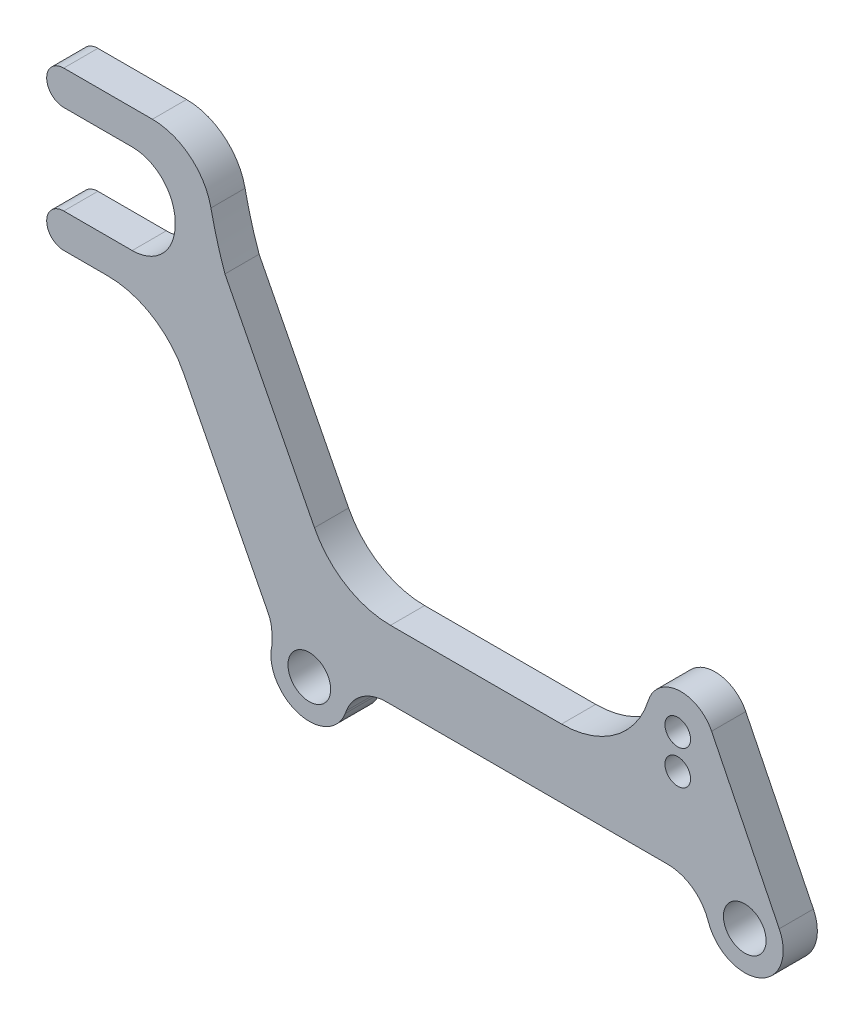
SolidWorks part; units mm, degrees
ref_plane "Front Plane" through (0, 0, 0) normal (0, 0, 1) x (1, 0, 0)
ref_plane "Top Plane" through (0, 0, 0) normal (0, 1, 0) x (1, 0, 0)
ref_plane "Right Plane" through (0, 0, 0) normal (1, 0, 0) x (0, 0, -1)
sketch "Sketch1" plane through (0, 0, 0) normal (0, 0, 1) x (1, 0, 0)
  line L0 (9.0217, 2) -> (41.9783, 2)
  line L1 (25.5, 14.9964) -> (25.5, -11.2721) construction
  line L2 (9.5048, 10.0021) -> (29.5383, 10.0021)
  line L3 (47.1152, 18.0606) -> (55.0364, 1.9894)
  line L4 (-4.3859, 1.0071) -> (-4.3847, 2.2692)
  line L5 (-4.8234, 4.0941) -> (-14.7192, 23.4447)
  line L6 (-4.3859, 1.0071) -> (-4.3839, 3.2346) construction
  line L7 (0.6015, 15.449) -> (-9.8806, 35.9461)
  line L8 (5.6141, 0.9982) -> (5.6183, 5.639) construction
  line L9 (-4.3839, 3.2346) -> (-15.5453, 25.06) construction
  line L10 (5.6183, 5.639) -> (-6.642, 29.6132) construction
  line L11 (-23.6226, 28.8915) -> (-28.7602, 28.8915)
  line L13 (-28.7602, 47.3915) -> (-18.3776, 47.3915)
  line L14 (-28.7602, 43.3915) -> (-20.7438, 43.3915)
  line L15 (-23.6226, 32.8915) -> (-28.7602, 32.8915)
  line L16 (-23.6226, 32.8915) -> (-20.7438, 32.8915)
  line L17 (-28.7602, 43.3915) -> (-28.7602, 32.8915) construction
  line L18 (-28.7602, 38.1415) -> (-33.6393, 38.1415) construction
  line L19 (-28.7602, 43.3915) -> (-18.3776, 43.3915) construction
  line L20 (46.6567, -1.2359) -> (46.7894, -1.5877)
  line L21 (4.3433, -1.2359) -> (4.2106, -1.5877)
  circle A0 centre (0, 0) radius 2.5
  circle A1 centre (51, 0) radius 2.5
  arc A2 (-4.3859, 1.0071) -> (4.2106, -1.5877) centre (0, 0) ccw
  arc A3 (46.7894, -1.5877) -> (55.0364, 1.9894) centre (51, 0) ccw
  circle A6 centre (43.1502, 12) radius 1.5
  circle A7 centre (43.1502, 16) radius 1.5
  arc A8 (47.1152, 18.0606) -> (39.7088, 17.4834) centre (43.5274, 16.2922) ccw
  arc A9 (39.7088, 17.4834) -> (29.5383, 10.0021) centre (29.5383, 20.656) cw
  arc A10 (-4.3847, 2.2692) -> (-4.8234, 4.0941) centre (-8.3847, 2.2728) ccw
  circle A11 centre (51, 0) radius 4.5 construction
  arc A12 (9.5048, 10.0021) -> (0.6015, 15.449) centre (9.5048, 20.0021) cw
  circle A14 centre (0, 0) radius 4.5 construction
  arc A15 (-14.7192, 23.4447) -> (-23.6226, 28.8915) centre (-23.6226, 18.8915) ccw
  arc A16 (-11.5244, 41.8176) -> (-18.3776, 47.3915) centre (-18.3776, 40.3915) ccw
  arc A17 (-16.0925, 40.2261) -> (-16.0925, 36.0569) centre (-21.3776, 38.1415) cw
  arc A18 (-15.3776, 40.3915) -> (-18.3776, 43.3915) centre (-18.3776, 40.3915) ccw construction
  arc A19 (-28.7602, 47.3915) -> (-28.7602, 43.3915) centre (-28.7602, 45.3915) ccw
  arc A20 (-28.7602, 28.8915) -> (-28.7602, 32.8915) centre (-28.7602, 30.8915) cw
  arc A21 (-16.0925, 36.0569) -> (-20.7438, 32.8915) centre (-20.7438, 37.8915) cw
  arc A22 (-20.7438, 43.3915) -> (-16.0925, 40.2261) centre (-20.7438, 38.3915) cw
  arc A23 (-11.3776, 40.3915) -> (-18.3776, 47.3915) centre (-18.3776, 40.3915) ccw construction
  arc A24 (-9.8806, 35.9461) -> (-11.5244, 41.8176) centre (32.5318, 50.9854) cw
  arc A25 (4.3433, -1.2359) -> (9.0217, 2) centre (9.0217, -3) cw
  arc A26 (46.6567, -1.2359) -> (41.9783, 2) centre (41.9783, -3) ccw
  point P9 (3.6661, 2.5112)
  point P10 (47.3339, 2.5112)
  point P25 (25.5, 2)
  point P33 (55.5, 0)
  point P36 (4.5, 0)
  point P47 (5.5634, 2)
  point P75 (45.4366, 2)
  point P76 (0, 0)
  point P77 (0, 0)
  dimension "D1" = 5
  dimension "D2" = 3
  dimension "D6" = 10
  dimension "D7" = 4
  dimension "D8" = 4
  dimension "D9" = 10
  dimension "D11" = 45
  dimension "D10" = 7
  dimension "D15" = 4
  dimension "D16" = 5
  dimension "D14" = 5
  dimension "D3" = 51
  dimension "D5" = 10
  dimension "D13" = 10.5
  dimension "D17" = 12
  dimension "D4" = 2
  dimension "D12" = 4
extrude "Boss-Extrude1" add sketch "Sketch1" along normal blind 4
